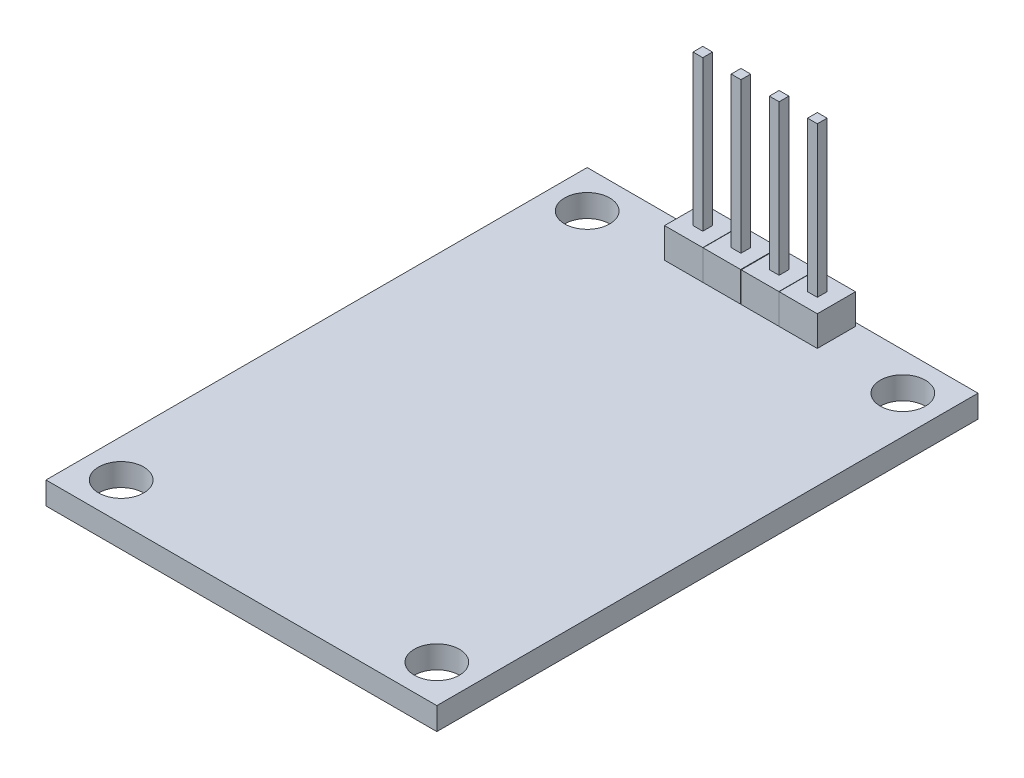
SolidWorks part; units mm, degrees
ref_plane "Ön Düzlem" through (0, 0, 0) normal (0, 0, 1) x (1, 0, 0)
ref_plane "Üst Düzlem" through (0, 0, 0) normal (0, 1, 0) x (1, 0, 0)
ref_plane "Sağ Düzlem" through (0, 0, 0) normal (1, 0, 0) x (0, 0, -1)
sketch "Sketch1" plane through (0, 0, 0) normal (0, 1, 0) x (1, 0, 0)
  line L1 (-13, 18) -> (13, 18)
  line L2 (-13, 18) -> (-13, -18)
  line L3 (-13, -18) -> (13, -18)
  line L4 (13, 18) -> (13, -18)
  line L5 (-13, 18) -> (13, -18) construction
  line L6 (-13, -18) -> (13, 18) construction
  point P0 (0, 0)
  dimension "D1" = 26
  dimension "D2" = 36
extrude "Boss-Extrude1" add sketch "Sketch1" along normal blind 1.5
sketch "Sketch2" plane through (0, 1.5, 0) normal (0, 1, 0) x (1, 0, 0)
  line L1 (-10.5, 15.5) -> (10.5, 15.5) construction
  line L2 (-10.5, 15.5) -> (-10.5, -15.5) construction
  line L3 (-10.5, -15.5) -> (10.5, -15.5) construction
  line L4 (10.5, 15.5) -> (10.5, -15.5) construction
  line L5 (-10.5, 15.5) -> (10.5, -15.5) construction
  line L6 (-10.5, -15.5) -> (10.5, 15.5) construction
  circle A0 centre (-10.5, 15.5) radius 1.5
  circle A1 centre (10.5, 15.5) radius 1.5
  circle A2 centre (10.5, -15.5) radius 1.5
  circle A3 centre (-10.5, -15.5) radius 1.5
  point P0 (0, 0)
  dimension "D3" = 3
  dimension "D4" = 3
  dimension "D5" = 3
  dimension "D6" = 3
  dimension "D1" = 31
  dimension "D2" = 21
extrude "Cut-Extrude1" cut sketch "Sketch2" against normal blind 1.5
sketch "Sketch3" plane through (0, 1.5, 0) normal (0, 1, 0) x (1, 0, 0)
  line L0 (-13, 16.5) -> (13, 16.5) construction
  line L1 (-13, 18) -> (-13, -18) construction
  line L2 (13, -18) -> (13, 18) construction
  line L3 (13, 18) -> (-13, 18) construction
  line L4 (0.02, 17.77) -> (2.52, 17.77)
  line L5 (0.02, 17.77) -> (0.02, 15.23)
  line L6 (0.02, 15.23) -> (2.52, 15.23)
  line L7 (2.52, 17.77) -> (2.52, 15.23)
  line L8 (0.02, 17.77) -> (2.52, 15.23) construction
  line L9 (0.02, 15.23) -> (2.52, 17.77) construction
  line L10 (0, 16.5) -> (0, 9.996) construction
  line L11 (-2.54, 15.23) -> (-5.08, 15.23)
  line L12 (2.54, 17.77) -> (5.08, 17.77)
  line L13 (2.54, 17.77) -> (2.54, 15.23)
  line L14 (2.54, 15.23) -> (5.08, 15.23)
  line L15 (5.08, 17.77) -> (5.08, 15.23)
  line L16 (2.54, 17.77) -> (5.08, 15.23) construction
  line L17 (2.54, 15.23) -> (5.08, 17.77) construction
  line L18 (-5.08, 17.77) -> (-5.08, 15.23)
  line L19 (-2.54, 17.77) -> (-5.08, 17.77)
  line L20 (-2.54, 17.77) -> (-2.54, 15.23)
  line L21 (-0.02, 15.23) -> (-2.52, 15.23)
  line L22 (-2.52, 17.77) -> (-2.52, 15.23)
  line L23 (-0.02, 17.77) -> (-2.52, 17.77)
  line L24 (-0.02, 17.77) -> (-0.02, 15.23)
  point P6 (1.27, 16.5)
  point P17 (3.81, 16.5)
  dimension "D1" = 2.5
  dimension "D2" = 2.54
  dimension "D3" = 1.5
  dimension "D4" = 1.27
  dimension "D5" = 2.54
  dimension "D6" = 2.54
  dimension "D7" = 2.54
extrude "Boss-Extrude2" add sketch "Sketch3" along normal blind 2
sketch "Sketch4" plane through (0, 3.5, 0) normal (0, 1, 0) x (1, 0, 0)
  line L0 (-5.08, 16.5) -> (-2.54, 16.5) construction
  line L1 (-5.08, 17.77) -> (-5.08, 15.23) construction
  line L2 (-2.54, 15.23) -> (-2.54, 17.77) construction
  line L3 (-2.54, 16.5) -> (-2.52, 16.5) construction
  line L4 (-2.52, 17.77) -> (-2.52, 15.23) construction
  line L5 (-2.52, 16.5) -> (-0.02, 16.5) construction
  line L6 (-0.02, 15.23) -> (-0.02, 17.77) construction
  line L7 (-0.02, 16.5) -> (0.02, 16.5) construction
  line L8 (0.02, 17.77) -> (0.02, 15.23) construction
  line L9 (0.02, 16.5) -> (2.52, 16.5) construction
  line L10 (2.52, 15.23) -> (2.52, 17.77) construction
  line L11 (2.52, 16.5) -> (2.54, 16.5) construction
  line L12 (2.54, 17.77) -> (2.54, 15.23) construction
  line L13 (2.54, 16.5) -> (5.08, 16.5) construction
  line L14 (5.08, 15.23) -> (5.08, 17.77) construction
  line L16 (-4.135, 16.825) -> (-3.485, 16.825)
  line L17 (-4.135, 16.825) -> (-4.135, 16.175)
  line L18 (-4.135, 16.175) -> (-3.485, 16.175)
  line L19 (-3.485, 16.825) -> (-3.485, 16.175)
  line L20 (-4.135, 16.825) -> (-3.485, 16.175) construction
  line L21 (-4.135, 16.175) -> (-3.485, 16.825) construction
  line L22 (-1.595, 16.825) -> (-0.945, 16.825)
  line L23 (-1.595, 16.825) -> (-1.595, 16.175)
  line L24 (-1.595, 16.175) -> (-0.945, 16.175)
  line L25 (-0.945, 16.825) -> (-0.945, 16.175)
  line L26 (-1.595, 16.825) -> (-0.945, 16.175) construction
  line L27 (-1.595, 16.175) -> (-0.945, 16.825) construction
  line L28 (0.945, 16.825) -> (1.595, 16.825)
  line L29 (0.945, 16.825) -> (0.945, 16.175)
  line L30 (0.945, 16.175) -> (1.595, 16.175)
  line L31 (1.595, 16.825) -> (1.595, 16.175)
  line L32 (0.945, 16.825) -> (1.595, 16.175) construction
  line L33 (0.945, 16.175) -> (1.595, 16.825) construction
  line L34 (3.485, 16.825) -> (4.135, 16.825)
  line L35 (3.485, 16.825) -> (3.485, 16.175)
  line L36 (3.485, 16.175) -> (4.135, 16.175)
  line L37 (4.135, 16.825) -> (4.135, 16.175)
  line L38 (3.485, 16.825) -> (4.135, 16.175) construction
  line L39 (3.485, 16.175) -> (4.135, 16.825) construction
  point P6 (-3.81, 16.5)
  point P29 (-1.27, 16.5)
  point P34 (1.27, 16.5)
  point P39 (3.81, 16.5)
  dimension "D1" = 0.65
  dimension "D2" = 0.65
  dimension "D3" = 0.65
  dimension "D4" = 0.65
  dimension "D5" = 0.65
  dimension "D6" = 0.65
  dimension "D7" = 0.65
  dimension "D8" = 0.65
extrude "Boss-Extrude3" add sketch "Sketch4" along normal blind 10 and the other way blind 5
sketch "Sketch5" plane through (0, 0, 0) normal (0, -1, 0) x (1, 0, 0)
  line L0 (-13, 18) -> (13, 18) construction
  line L1 (-7.5, 6.5) -> (7.5, 6.5)
  line L2 (-7.5, 6.5) -> (-7.5, -5)
  line L3 (-7.5, -5) -> (7.5, -5)
  line L4 (7.5, 6.5) -> (7.5, -5)
  line L5 (-7.5, 6.5) -> (7.5, -5) construction
  line L6 (-7.5, -5) -> (7.5, 6.5) construction
  point P0 (0, 0.75)
  dimension "D1" = 15
  dimension "D2" = 11.5
  dimension "D3" = 11.5
extrude "Boss-Extrude4" add sketch "Sketch5" along normal blind 2.5
sketch "Sketch6" plane through (0, 0, 0) normal (0, -1, 0) x (1, 0, 0)
  line L1 (0.162, -10.3844) -> (1.9956, -10.3844)
  line L2 (0.162, -10.3844) -> (0.162, -11.6747)
  line L3 (0.162, -11.6747) -> (1.9956, -11.6747)
  line L4 (1.9956, -10.3844) -> (1.9956, -11.6747)
  line L5 (0.162, -10.3844) -> (1.9956, -11.6747) construction
  line L6 (0.162, -11.6747) -> (1.9956, -10.3844) construction
  line L7 (2.4709, -10.3844) -> (4.4403, -10.3844)
  line L8 (2.4709, -10.3844) -> (2.4709, -11.6747)
  line L9 (2.4709, -11.6747) -> (4.4403, -11.6747)
  line L10 (4.4403, -10.3844) -> (4.4403, -11.6747)
  line L11 (2.4709, -10.3844) -> (4.4403, -11.6747) construction
  line L12 (2.4709, -11.6747) -> (4.4403, -10.3844) construction
  line L13 (4.9836, -10.3844) -> (6.6813, -10.3844)
  line L14 (4.9836, -10.3844) -> (4.9836, -11.6747)
  line L15 (4.9836, -11.6747) -> (6.6813, -11.6747)
  line L16 (6.6813, -10.3844) -> (6.6813, -11.6747)
  line L17 (4.9836, -10.3844) -> (6.6813, -11.6747) construction
  line L18 (4.9836, -11.6747) -> (6.6813, -10.3844) construction
  line L19 (7.2585, -10.3844) -> (8.8205, -10.3844)
  line L20 (7.2585, -10.3844) -> (7.2585, -11.6747)
  line L21 (7.2585, -11.6747) -> (8.8205, -11.6747)
  line L22 (8.8205, -10.3844) -> (8.8205, -11.6747)
  line L23 (7.2585, -10.3844) -> (8.8205, -11.6747) construction
  line L24 (7.2585, -11.6747) -> (8.8205, -10.3844) construction
  point P0 (1.0788, -11.0295)
  point P5 (3.4556, -11.0295)
  point P10 (5.8324, -11.0295)
  point P15 (8.0395, -11.0295)
extrude "Boss-Extrude5" add sketch "Sketch6" along normal blind 1.5
fillet "Fillet1" radius 0.5 4 edges at (0, -2.5, -5) (-7.5, -2.5, 0.75) (0, -2.5, 6.5) (7.5, -2.5, 0.75)
sketch "Sketch7" plane through (0, -2.5, 0) normal (0, -1, 0) x (1, 0, 0)
  line L0 (-4.6766, -1.8606) -> (5.1292, -1.8606) construction
  text T0 "GPS"
extrude "Cut-Extrude2" cut sketch "Sketch7" against normal blind 0.5
